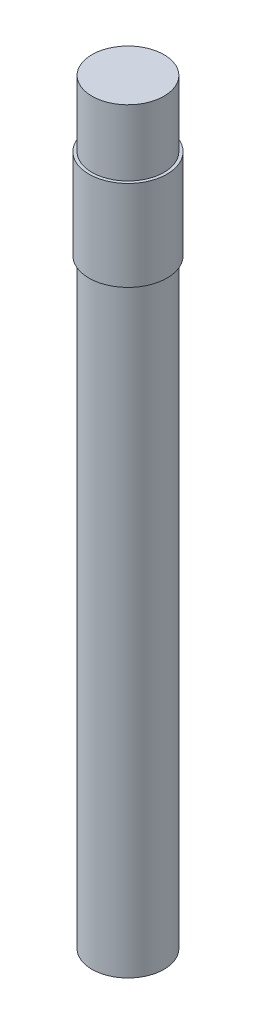
SolidWorks part; units mm, degrees
ref_plane "Front" through (0, 0, 0) normal (0, 0, 1) x (1, 0, 0)
ref_plane "Top" through (0, 0, 0) normal (0, 1, 0) x (1, 0, 0)
ref_plane "Right" through (0, 0, 0) normal (1, 0, 0) x (0, 0, -1)
sketch "Эскиз1" plane through (0, 0, 0) normal (0, 1, 0) x (1, 0, 0)
  circle A0 centre (0, 0) radius 6
  dimension "D1" = 12
extrude "База" add sketch "Эскиз1" along normal blind 100
sketch "Эскиз2" plane through (0, 100, 0) normal (0, 1, 0) x (1, 0, 0)
  circle A0 centre (0, 0) radius 6.5
  dimension "D1" = 13
extrude "Бобышка-Вытянуть2" add sketch "Эскиз2" along normal blind 15
sketch "Эскиз3" plane through (0, 115, 0) normal (0, 1, 0) x (1, 0, 0)
  circle A0 centre (0, 0) radius 6
  dimension "D1" = 12
extrude "Бобышка-Вытянуть3" add sketch "Эскиз3" along normal blind 11
sketch "Эскиз4" plane through (0, 0, 0) normal (0, -1, 0) x (1, 0, 0)
  circle A0 centre (0, 0) radius 5.5
  dimension "D1" = 11
extrude "Вырез-Вытянуть1" cut sketch "Эскиз4" against normal blind 2
sketch "Эскиз5" plane through (0, 2, 0) normal (0, -1, 0) x (1, 0, 0)
  circle A0 centre (0, 0) radius 3.5
  circle A1 centre (0, 0) radius 0.75
  dimension "D1" = 7
  dimension "D2" = 1.5
extrude "Объектив" add sketch "Эскиз5" along normal blind 2
sketch "Эскиз6" plane through (0, 2, 0) normal (0, -1, 0) x (1, 0, 0)
  line L0 (0, 4.5) -> (0, 5.5) construction
  line L1 (-0.75, 4.9) -> (0.75, 4.9)
  line L2 (-0.75, 4.9) -> (-0.75, 4.1)
  line L3 (-0.75, 4.1) -> (0.75, 4.1)
  line L4 (0.75, 4.9) -> (0.75, 4.1)
  line L5 (-0.75, 4.9) -> (0.75, 4.1) construction
  line L6 (-0.75, 4.1) -> (0.75, 4.9) construction
  line L7 (0, 4.5) -> (0, 3.5) construction
  circle A0 centre (0, 0) radius 5.5 construction
  circle A1 centre (0, 0) radius 3.5 construction
  point P0 (0, 4.5)
  dimension "D1" = 1.5
  dimension "D2" = 0.8
extrude "Светодиод" add sketch "Эскиз6" along normal blind 1
pattern_circular "Круговой массив1" count 8 over 360 about axis through (0, 0, 0) along (0, 1, 0) of "Светодиод"
